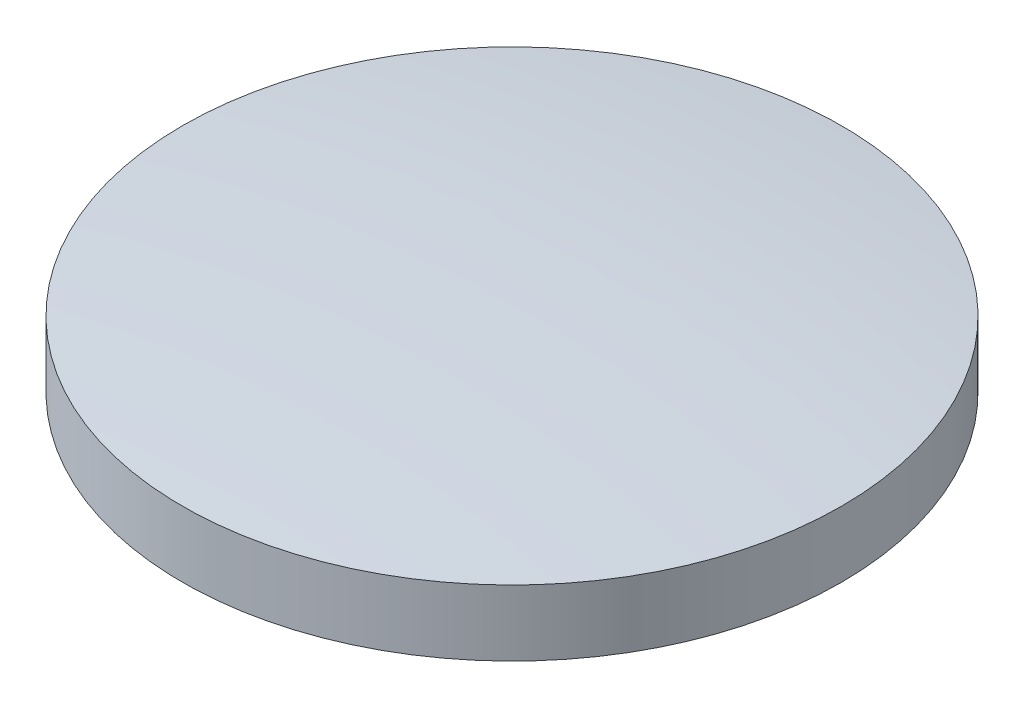
SolidWorks part; units mm, degrees
material "Glass"
ref_plane "Front" through (0, 0, 0) normal (0, 0, 1) x (1, 0, 0)
ref_plane "Top" through (0, 0, 0) normal (0, 1, 0) x (1, 0, 0)
ref_plane "Right" through (0, 0, 0) normal (1, 0, 0) x (0, 0, -1)
sketch "Sketch1" plane through (0, 0, 0) normal (0, 0, 1) x (1, 0, 0)
  line L0 (-10, 1) -> (10, 1) construction
  line L1 (10, 1) -> (10, -1) construction
  line L2 (10, -1) -> (-10, -1) construction
  line L3 (-10, -1) -> (-10, 1)
  line L4 (-10, 1) -> (10, -1) construction
  line L5 (0, 1.6) -> (0, -0.4094)
  line L6 (0, 1.6) -> (10, 1.6) construction
  line L7 (10, 1.6) -> (10, 1) construction
  arc A0 (-10, 1) -> (0, 1.6) centre (0, -82.0333) cw
  arc A1 (-10, -1) -> (0, -0.4094) centre (-0.0779, -84.0427) cw
  dimension "D1" = 20
  dimension "D2" = 2.6
  dimension "D3" = 0.6
revolve "Revolve1" add sketch "Sketch1" angle 360 about L5
